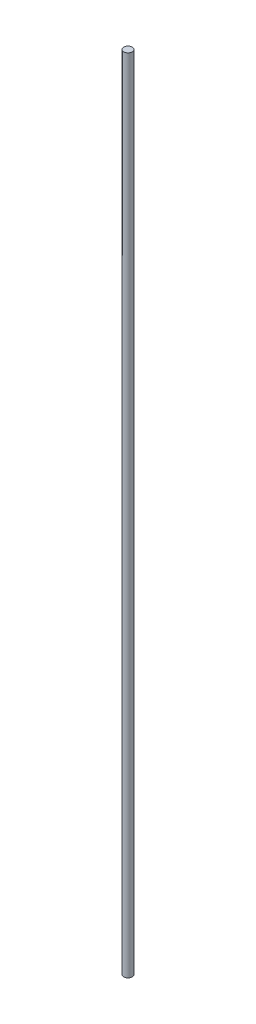
SolidWorks part; units mm, degrees
ref_plane "Front Plane" through (0, 0, 0) normal (0, 0, 1) x (1, 0, 0)
ref_plane "Top Plane" through (0, 0, 0) normal (0, 1, 0) x (1, 0, 0)
ref_plane "Right Plane" through (0, 0, 0) normal (1, 0, 0) x (0, 0, -1)
sketch "Sketch2" plane through (0, 0, 0) normal (0, 1, 0) x (1, 0, 0)
  circle A0 centre (0, 0) radius 1.5
  dimension "D1" = 3
extrude "Boss-Extrude1" add sketch "Sketch2" along normal blind 285
